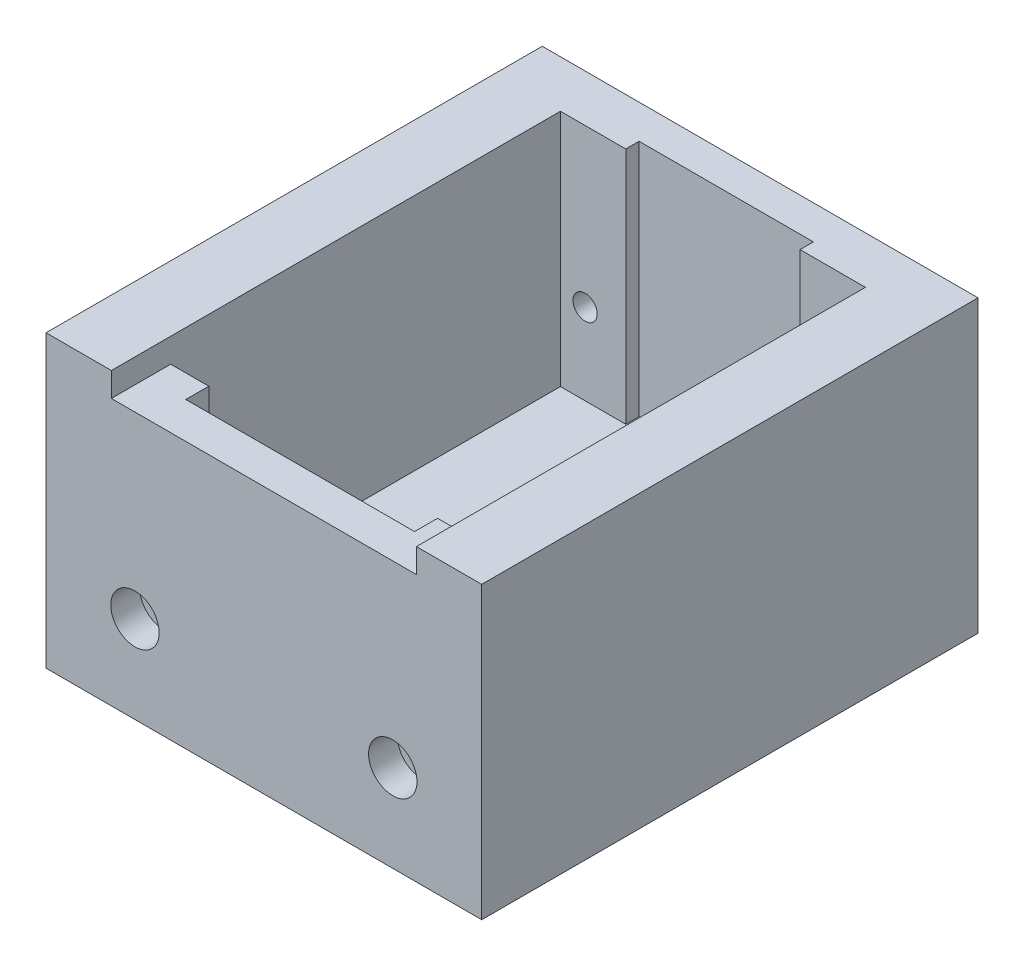
SolidWorks part; units mm, degrees
ref_plane "前视基准面" through (0, 0, 0) normal (0, 0, 1) x (1, 0, 0)
ref_plane "上视基准面" through (0, 0, 0) normal (0, 1, 0) x (1, 0, 0)
ref_plane "右视基准面" through (0, 0, 0) normal (1, 0, 0) x (0, 0, -1)
other "Configuration Table"
sketch "草图3" plane through (0, 0, 0) normal (0, 1, 0) x (1, 0, 0)
  line L1 (-18, -25) -> (18, -25)
  line L2 (-18, -25) -> (-18, 25)
  line L3 (-18, 25) -> (18, 25)
  line L4 (18, -25) -> (18, 25)
  line L5 (-18, -25) -> (18, 25) construction
  line L6 (-18, 25) -> (18, -25) construction
  point P0 (0, 0)
  dimension "D1" = 36
  dimension "D2" = 50
extrude "凸台-拉伸1" add sketch "草图3" along normal blind 24
sketch "草图4" plane through (0, 24, 0) normal (0, 1, 0) x (1, 0, 0)
  line L1 (-12.4, -15.9) -> (12.4, -15.9)
  line L2 (-12.4, -15.9) -> (-12.4, 15.9)
  line L3 (-12.4, 15.9) -> (12.4, 15.9)
  line L4 (12.4, -15.9) -> (12.4, 15.9)
  line L5 (-12.4, -15.9) -> (12.4, 15.9) construction
  line L6 (-12.4, 15.9) -> (12.4, -15.9) construction
  point P0 (0, 0)
  dimension "D1" = 24.8
  dimension "D2" = 31.8
extrude "切除-拉伸1" cut sketch "草图4" against normal blind 19.7
sketch "草图5" plane through (0, 24, 0) normal (0, 1, 0) x (1, 0, 0)
  line L0 (12.4, 15.9) -> (-12.4, 15.9) construction
  line L1 (-7, 14.8) -> (7, 14.8)
  line L2 (-7, 14.8) -> (-7, 17)
  line L3 (-7, 17) -> (7, 17)
  line L4 (7, 14.8) -> (7, 17)
  line L5 (-7, 14.8) -> (7, 17) construction
  line L6 (-7, 17) -> (7, 14.8) construction
  point P0 (0, 15.9)
  dimension "D1" = 14
  dimension "D2" = 2.2
extrude "切除-拉伸3" cut sketch "草图5" against normal blind 19.7 contours L3 L4 L1 L2
sketch "草图6" plane through (0, 24, 0) normal (0, 1, 0) x (1, 0, 0)
  line L0 (-12.4, -15.9) -> (12.4, -15.9) construction
  line L1 (-9.25, -17.8) -> (9.25, -17.8)
  line L2 (-9.25, -17.8) -> (-9.25, -14)
  line L3 (-9.25, -14) -> (9.25, -14)
  line L4 (9.25, -17.8) -> (9.25, -14)
  line L5 (-9.25, -17.8) -> (9.25, -14) construction
  line L6 (-9.25, -14) -> (9.25, -17.8) construction
  point P0 (0, -15.9)
  dimension "D1" = 18.5
  dimension "D2" = 3.8
extrude "切除-拉伸4" cut sketch "草图6" against normal blind 14.7
sketch "草图7" plane through (0, 24, 0) normal (0, 1, 0) x (1, 0, 0)
  line L0 (-18, -25) -> (18, -25) construction
  line L1 (-12.4, -37.1402) -> (12.4, -37.1402)
  line L2 (-12.4, -37.1402) -> (-12.4, -12.8598)
  line L3 (-12.4, -12.8598) -> (12.4, -12.8598)
  line L4 (12.4, -37.1402) -> (12.4, -12.8598)
  line L5 (-12.4, -37.1402) -> (12.4, -12.8598) construction
  line L6 (-12.4, -12.8598) -> (12.4, -37.1402) construction
  point P0 (0, -25)
  dimension "D1" = 24.8
extrude "切除-拉伸5" cut sketch "草图7" against normal blind 2
sketch "草图8" plane through (0, 0, 25) normal (0, 0, 1) x (1, 0, 0)
  line L0 (18, 24) -> (18, 0) construction
  line L1 (-18, 0) -> (18, 0) construction
  line L2 (-18, 24) -> (-18, 0) construction
  circle A0 centre (10.65, 7.2) radius 2
  circle A1 centre (-10.65, 7.2) radius 2
  dimension "D1" = 7.35
  dimension "D3" = 7.35
  dimension "D2" = 7.2
  dimension "D4" = 7.2
extrude "切除-拉伸6" cut sketch "草图8" against normal blind 6.4
sketch "草图9" plane through (0, 0, 18.6) normal (0, 0, 1) x (1, 0, 0)
  circle A0 centre (10.65, 7.2) radius 1
  circle A1 centre (-10.65, 7.2) radius 1
extrude "切除-拉伸7" cut sketch "草图9" against normal blind 6.4
sketch "草图10" plane through (0, 0, -25) normal (0, 0, -1) x (-1, 0, 0)
  line L0 (-18, 24) -> (-18, 0) construction
  line L1 (-18, 0) -> (18, 0) construction
  line L2 (18, 24) -> (18, 0) construction
  circle A0 centre (-10.565, 11) radius 2
  circle A1 centre (10.56, 11) radius 2
  dimension "D1" = 7.435
  dimension "D3" = 7.44
  dimension "D2" = 11
  dimension "D4" = 11
extrude "切除-拉伸8" cut sketch "草图10" against normal blind 7.4
sketch "草图11" plane through (0, 0, -17.6) normal (0, 0, -1) x (-1, 0, 0)
  circle A0 centre (10.56, 11) radius 1
  circle A1 centre (-10.565, 11) radius 1
extrude "切除-拉伸9" cut sketch "草图11" against normal blind 7.4
sketch "草图14" plane through (0, 0, 25) normal (0, 0, 1) x (1, 0, 0)
  line L1 (-26.5003, 33.3651) -> (21.1929, 33.3651)
  line L2 (-26.5003, 33.3651) -> (-26.5003, -8.5784)
  line L3 (-26.5003, -8.5784) -> (21.1929, -8.5784)
  line L4 (21.1929, 33.3651) -> (21.1929, -8.5784)
extrude "切除-拉伸12" cut sketch "草图14" against normal blind 4
sketch "草图16" plane through (0, 0, -25) normal (0, 0, -1) x (-1, 0, 0)
  line L1 (-33.7246, 32.2994) -> (35.4423, 32.2994)
  line L2 (-33.7246, 32.2994) -> (-33.7246, -7.1228)
  line L3 (-33.7246, -7.1228) -> (35.4423, -7.1228)
  line L4 (35.4423, 32.2994) -> (35.4423, -7.1228)
extrude "切除-拉伸13" cut sketch "草图16" against normal blind 5
sketch "草图18" plane through (0, 24, 0) normal (0, 1, 0) x (1, 0, 0)
  line L113 (-12.6, -16.1) -> (12.6, -16.1)
  line L114 (-12.6, 16.1) -> (-12.6, -16.1)
  line L115 (-7.2, 16.1) -> (-12.6, 16.1)
  line L116 (-7.2, 17.2) -> (-7.2, 16.1)
  line L117 (7.2, 17.2) -> (-7.2, 17.2)
  line L118 (7.2, 16.1) -> (7.2, 17.2)
  line L119 (12.6, 16.1) -> (7.2, 16.1)
  line L120 (12.6, -16.1) -> (12.6, 16.1)
  line L121 (-12.6, -16.1) -> (12.6, -16.1)
  line L122 (-12.6, 16.1) -> (-12.6, -16.1)
  line L123 (-7.2, 16.1) -> (-12.6, 16.1)
  line L124 (-7.2, 17.2) -> (-7.2, 16.1)
  line L125 (7.2, 17.2) -> (-7.2, 17.2)
  line L126 (7.2, 16.1) -> (7.2, 17.2)
  line L127 (12.6, 16.1) -> (7.2, 16.1)
  line L128 (12.6, -16.1) -> (12.6, 16.1)
  dimension "D1" = 0.2
extrude "切除-拉伸17" cut sketch "草图18" against normal blind 19.7
sketch "草图19" plane through (0, 22, 0) normal (0, 1, 0) x (1, 0, 0)
  line L14 (9.45, -18) -> (9.45, -15.9)
  line L15 (-9.45, -15.9) -> (-9.45, -18)
  line L16 (-9.45, -18) -> (9.45, -18)
  line L17 (9.45, -15.9) -> (-9.45, -15.9)
  line L18 (9.45, -18) -> (9.45, -15.9)
  line L19 (-9.45, -15.9) -> (-9.45, -18)
  line L20 (-9.45, -18) -> (9.45, -18)
  line L21 (9.45, -15.9) -> (-9.45, -15.9)
  dimension "D1" = 0.2
extrude "切除-拉伸18" cut sketch "草图19" against normal blind 12.7
sketch "草图20" plane through (0, 24, 0) normal (0, 1, 0) x (1, 0, 0)
  line L1 (-12.6, 16.1) -> (12.6, 16.1)
  line L2 (-12.6, 16.1) -> (-12.6, -22.1176)
  line L3 (-12.6, -22.1176) -> (12.6, -22.1176)
  line L4 (12.6, 16.1) -> (12.6, -22.1176)
extrude "切除-拉伸19" cut sketch "草图20" against normal up to surface (2 mm away) up to face at (0, 22, 17.8)
